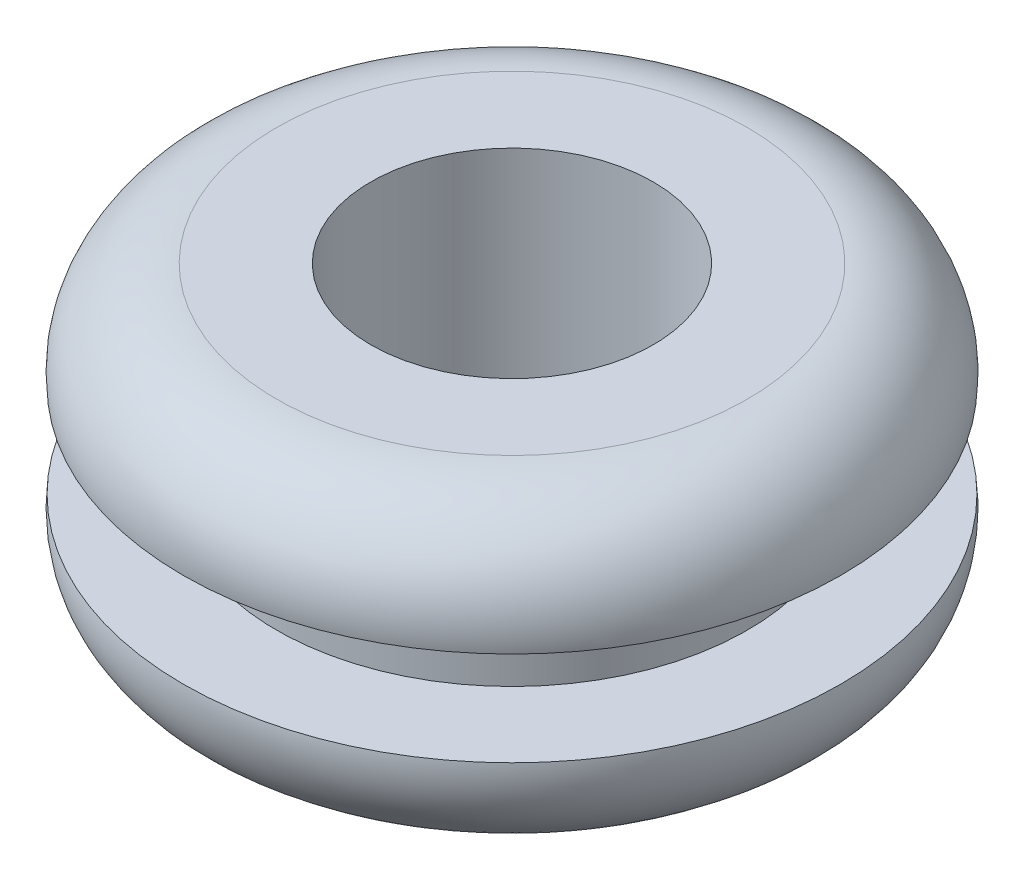
SolidWorks part; units mm, degrees
ref_plane "Front" through (0, 0, 0) normal (0, 0, 1) x (1, 0, 0)
ref_plane "Top" through (0, 0, 0) normal (0, 1, 0) x (1, 0, 0)
ref_plane "Right" through (0, 0, 0) normal (1, 0, 0) x (0, 0, -1)
sketch "Sketch1" plane through (0, 0, 0) normal (1, 0, 0) x (0, 0, -1)
  line L0 (0, -5.1594) -> (0, 5.1594) construction
  line L1 (0, 1.5875) -> (0, -1.5875) construction
  line L2 (-11.1125, 5.1594) -> (11.1125, 5.1594) construction
  line L3 (-4.7625, 1.5875) -> (4.7625, 1.5875) construction
  line L4 (-7.9375, 0) -> (7.9375, 0) construction
  point P12 (-4.7625, 1.5875)
  point P13 (4.7625, 1.5875)
  point P14 (-7.9375, 0)
  point P15 (7.9375, 0)
  point P16 (-11.1125, 5.1594)
  point P17 (0, -5.1594)
  point P18 (11.1125, 5.1594)
  point P19 (0, 5.1594)
  point P20 (0, 1.5875)
  point P21 (0, -1.5875)
  dimension "Overall Height E" = 10.3187
  dimension "Material Thickness B" = 3.175
  dimension "Flange Diameter D" = 22.225
  dimension "ID C" = 9.525
  dimension "For ID A" = 15.875
sketch "Sketch2" plane through (0, 0, 0) normal (1, 0, 0) x (0, 0, -1)
  line L0 (-4.7625, -5.1594) -> (-4.7625, 5.1594)
  line L1 (-4.7625, 5.1594) -> (-7.9375, 5.1594)
  line L2 (-7.9375, 1.5875) -> (-7.9375, -1.5875)
  line L3 (-7.9375, 1.5875) -> (-11.0876, 1.5875)
  line L4 (-7.9375, -1.5875) -> (-11.0876, -1.5875)
  line L5 (-4.7625, -5.1594) -> (-7.9375, -5.1594)
  arc A0 (-11.0876, 1.5875) -> (-7.9375, 5.1594) centre (-7.9375, 1.9844) cw
  arc A1 (-11.0876, -1.5875) -> (-7.9375, -5.1594) centre (-7.9375, -1.9844) ccw
  point P4 (-11.1125, 1.9844)
revolve "Revolve1" add sketch "Sketch2" angle 360 about L0
ref_plane "Plane1" through (0, 5.1594, 0) normal (0, -1, 0) x (0, 0, -1)
sketch "Sketch3" plane through (0, 5.1594, 0) normal (0, -1, 0) x (0, 0, -1)
  line L0 (0, -11.1125) -> (0, 11.1125) construction
  line L1 (-11.1125, 0) -> (11.1125, 0) construction
  line L2 (0, 4.7625) -> (0, -4.7625) construction
  line L3 (-4.7625, 0) -> (4.7625, 0) construction
  line L4 (0, 7.9375) -> (0, -7.9375) construction
  line L5 (-7.9375, 0) -> (7.9375, 0) construction
  point P11 (0, 11.1125)
  point P12 (0, 4.7625)
  point P13 (0, -4.7625)
  point P14 (0, -11.1125)
  point P19 (0, -7.9375)
  point P20 (0, 7.9375)
